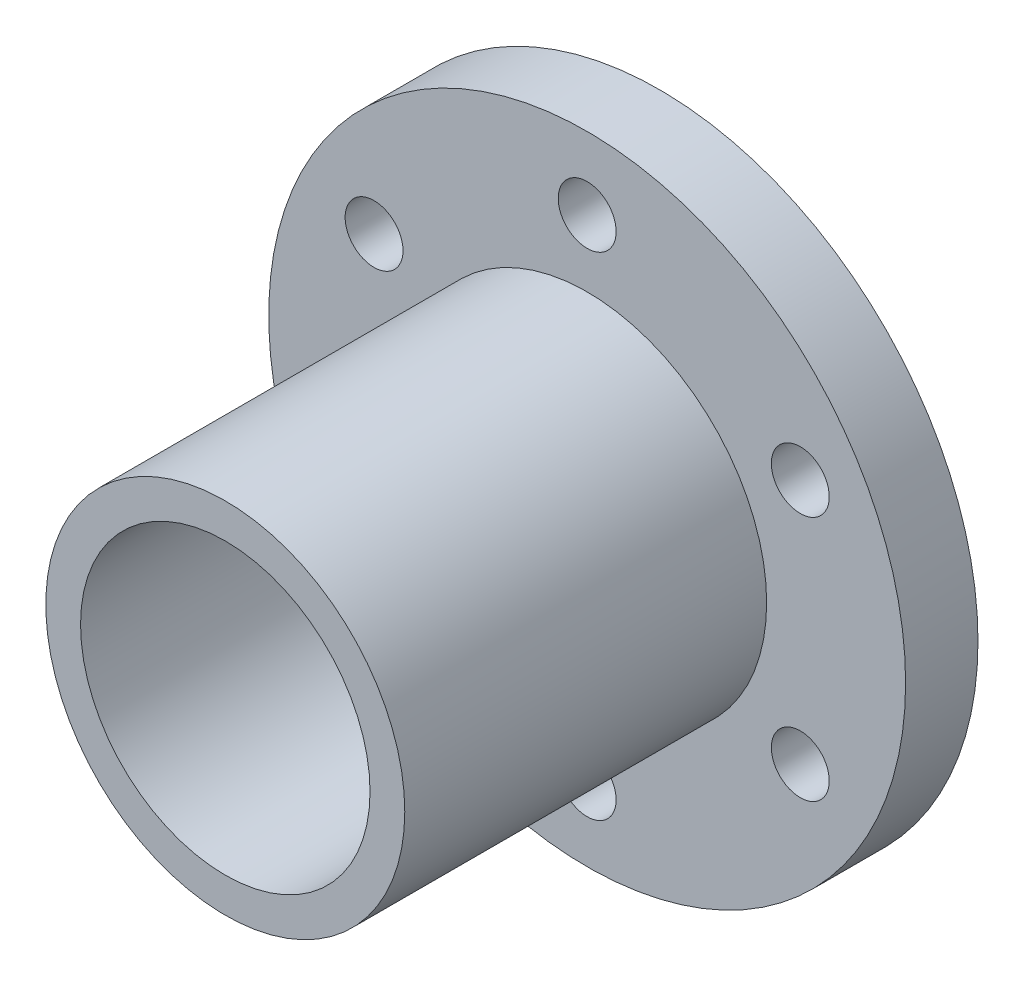
SolidWorks part; units mm, degrees
ref_plane "Front Plane" through (0, 0, 0) normal (0, 0, 1) x (1, 0, 0)
ref_plane "Top Plane" through (0, 0, 0) normal (0, 1, 0) x (1, 0, 0)
ref_plane "Right Plane" through (0, 0, 0) normal (1, 0, 0) x (0, 0, -1)
sketch "Sketch1" plane through (0, 0, 0) normal (0, 0, 1) x (1, 0, 0)
  circle A0 centre (0, 0) radius 110
  dimension "D1" = 220
extrude "Boss-Extrude1" add sketch "Sketch1" along normal blind 25
sketch "Sketch2" plane through (0, 0, 25) normal (0, 0, 1) x (1, 0, 0)
  circle A0 centre (0, 0) radius 62
  dimension "D1" = 124
extrude "Boss-Extrude2" add sketch "Sketch2" along normal blind 125
sketch "Sketch3" plane through (0, 0, 150) normal (0, 0, 1) x (1, 0, 0)
  circle A0 centre (0, 0) radius 50
  dimension "D1" = 100
extrude "Cut-Extrude1" cut sketch "Sketch3" against normal through all
sketch "Sketch4" plane through (0, 0, 25) normal (0, 0, 1) x (1, 0, 0)
  circle A0 centre (0, 0) radius 85 construction
  circle A1 centre (0, 85) radius 10
  circle A2 centre (73.6122, 42.5) radius 10
  circle A3 centre (73.6122, -42.5) radius 10
  circle A4 centre (0, -85) radius 10
  circle A5 centre (-73.6122, -42.5) radius 10
  circle A6 centre (-73.6122, 42.5) radius 10
  point P6 (0, 0)
  point P17 (0, 0)
  dimension "D1" = 170
  dimension "D2" = 20
  dimension "D3" = 6
extrude "Cut-Extrude2" cut sketch "Sketch4" against normal through all
